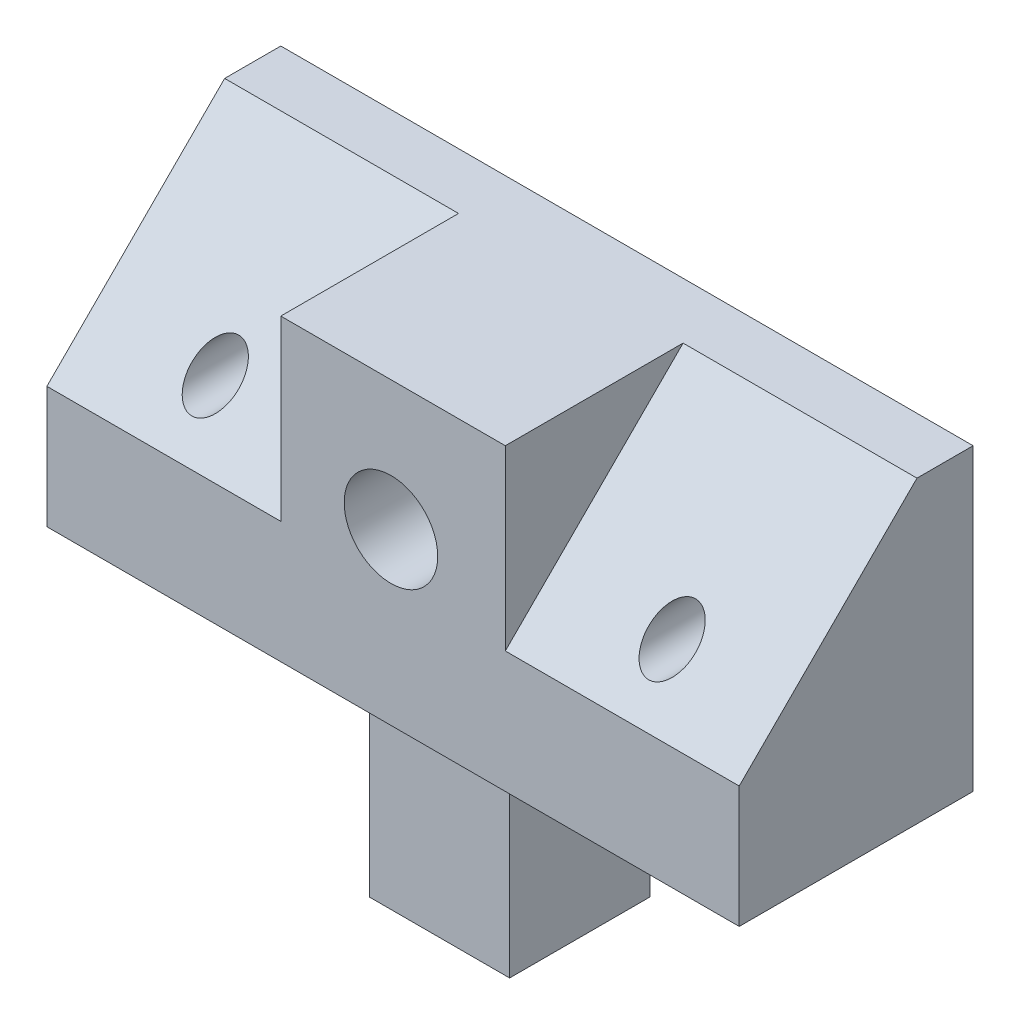
SolidWorks part; units mm, degrees
ref_plane "Front Plane" through (0, 0, 0) normal (0, 0, 1) x (1, 0, 0)
ref_plane "Top Plane" through (0, 0, 0) normal (0, 1, 0) x (1, 0, 0)
ref_plane "Right Plane" through (0, 0, 0) normal (1, 0, 0) x (0, 0, -1)
sketch "Sketch2" plane through (0, 0, 0) normal (0, 0, 1) x (1, 0, 0)
  line L10 (0, 0) -> (74, 0)
  line L11 (0, 0) -> (0, 32)
  line L12 (0, 32) -> (74, 32)
  line L13 (74, 0) -> (74, 32)
  line L14 (0, 0) -> (74, 32) construction
  line L15 (0, 32) -> (74, 0) construction
  point P5 (37, 16)
  dimension "D1" = 32
  dimension "D2" = 74
extrude "Boss-Extrude1" add sketch "Sketch2" along normal blind 25
sketch "Sketch4" plane through (0, 0, 0) normal (-1, 0, 0) x (0, 0, 1)
  line L0 (25, 32) -> (6, 32)
  line L1 (25, 32) -> (0, 32) construction
  line L2 (25, 32) -> (25, 13)
  line L3 (25, 32) -> (25, 0) construction
  line L4 (6, 32) -> (25, 13)
  dimension "D1" = 13
  dimension "D2" = 6
extrude "Cut-Extrude2" cut sketch "Sketch4" against normal blind 25
sketch "Sketch5" plane through (74, 0, 0) normal (1, 0, 0) x (0, 0, -1)
  line L0 (-25, 32) -> (-6, 32)
  line L1 (-25, 32) -> (0, 32) construction
  line L2 (-6, 32) -> (-25, 13)
  line L3 (-25, 0) -> (-25, 32) construction
  line L4 (-25, 13) -> (-25, 32)
  dimension "D1" = 13
  dimension "D2" = 6
extrude "Cut-Extrude3" cut sketch "Sketch5" against normal blind 25
sketch "Sketch6" plane through (0, 0, 25) normal (0, 0, 1) x (1, 0, 0)
  line L0 (49, 32) -> (25, 32) construction
  line L1 (25, 13) -> (0, 13) construction
  line L2 (25, 13) -> (25, 32) construction
  line L3 (49, 13) -> (74, 13) construction
  line L4 (49, 32) -> (49, 13) construction
  circle A0 centre (36.7751, 18.1364) radius 5
  circle A1 centre (13, 18) radius 2.5
  circle A2 centre (61.8308, 18) radius 2.5
  point P5 (37, 32)
  point P17 (0, 0)
  dimension "D1" = 10
  dimension "D3" = 5
  dimension "D5" = 5
  dimension "D8" = 5
  dimension "D2" = 13.8636
  dimension "D4" = 12
  dimension "D6" = 5
  dimension "D7" = 12.8308
extrude "Cut-Extrude4" cut sketch "Sketch6" against normal blind 33
sketch "Sketch7" plane through (0, 0, 0) normal (0, -1, 0) x (1, 0, 0)
  line L1 (74, 25) -> (74, 0) construction
  line L7 (29.5, 5.0414) -> (44.5, 5.0414)
  line L8 (29.5, 5.0414) -> (29.5, 20.0414)
  line L9 (29.5, 20.0414) -> (44.5, 20.0414)
  line L10 (44.5, 5.0414) -> (44.5, 20.0414)
  line L11 (29.5, 5.0414) -> (44.5, 20.0414) construction
  line L12 (29.5, 20.0414) -> (44.5, 5.0414) construction
  point P12 (37, 12.5414)
  dimension "D1" = 15
  dimension "D2" = 15
  dimension "D3" = 37
extrude "Boss-Extrude2" add sketch "Sketch7" along normal blind 22
